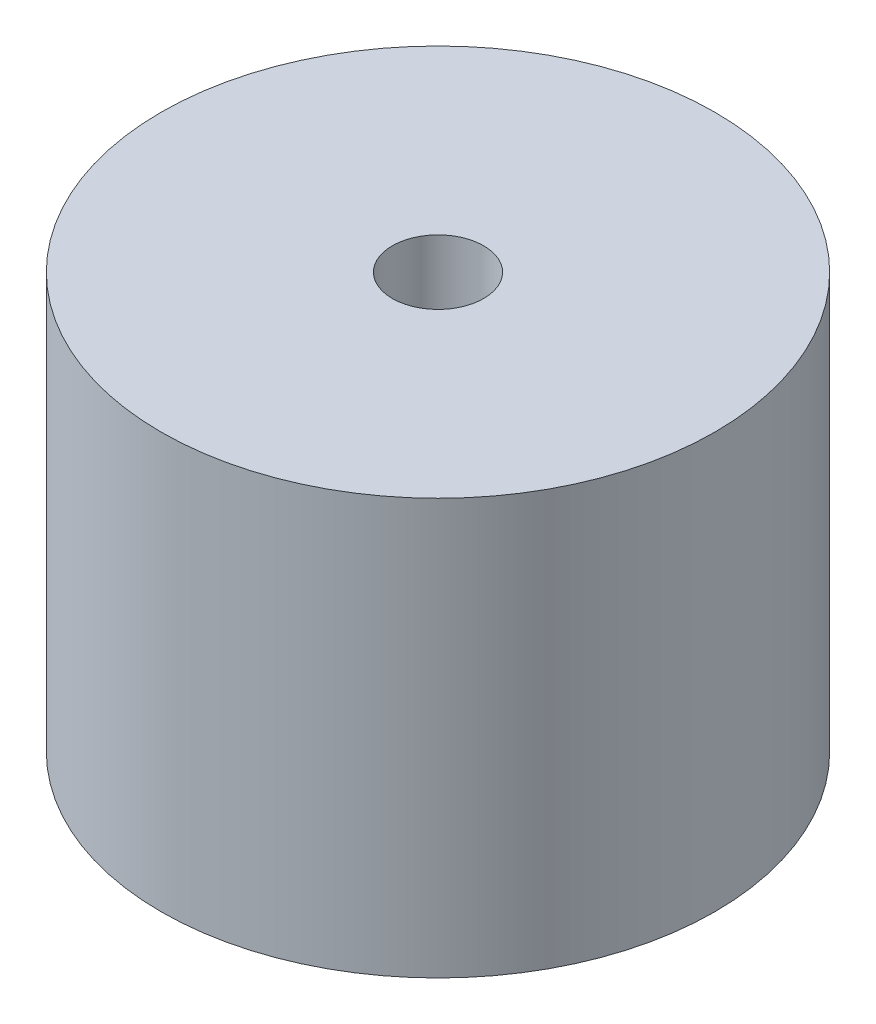
SolidWorks part; units mm, degrees
ref_plane "Płaszczyzna przednia" through (0, 0, 0) normal (0, 0, 1) x (1, 0, 0)
ref_plane "Płaszczyzna górna" through (0, 0, 0) normal (0, 1, 0) x (1, 0, 0)
ref_plane "Płaszczyzna prawa" through (0, 0, 0) normal (1, 0, 0) x (0, 0, -1)
sketch "Szkic1" plane through (0, 0, 0) normal (0, 1, 0) x (1, 0, 0)
  circle A0 centre (0, 0) radius 10
  dimension "D1" = 20
extrude "Dodanie-wyciągnięcie1" add sketch "Szkic1" along normal blind 15
hole_wizard "Otwór gwintowany M41" positions "Szkic2" profile "Szkic3" hole size "M4" standard "DIN"
sketch "Szkic2" plane through (0, 15, 0) normal (0, 1, 0) x (1, 0, 0)
  point P0 (0, 0)
sketch "Szkic3" plane through (0, 15, 0) normal (1, 0, 0) x (0, 0, 1)
  line L0 (0, 0) -> (0, 5.9914)
  line L1 (0, 5.9914) -> (1.65, 5)
  line L2 (1.65, 5) -> (1.65, 0)
  line L5 (1.65, 0) -> (0, 0)
  line L10 (0, 5.9914) -> (-1.65, 5) construction
  line L11 (0, -6.35) -> (0, 107.95) construction
  dimension "Średnica otworu" = 3.3
  dimension "Głębokość otworu" = 5
  dimension "Kąt wiertła" = 118
